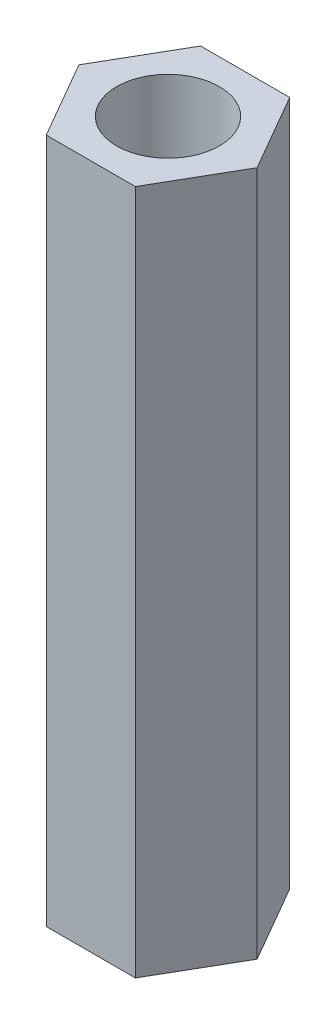
SolidWorks part; units mm, degrees
material "黄铜"
ref_plane "前视基准面" through (0, 0, 0) normal (0, 0, 1) x (1, 0, 0)
ref_plane "上视基准面" through (0, 0, 0) normal (0, 1, 0) x (1, 0, 0)
ref_plane "右视基准面" through (0, 0, 0) normal (1, 0, 0) x (0, 0, -1)
other "Configuration Table"
sketch "草图1" plane through (0, 0, 0) normal (0, 1, 0) x (1, 0, 0)
  line L1 (2.6, 0) -> (1.3, 2.2517)
  line L2 (1.3, 2.2517) -> (-1.3, 2.2517)
  line L3 (-1.3, 2.2517) -> (-2.6, 0)
  line L4 (-2.6, 0) -> (-1.3, -2.2517)
  line L5 (-1.3, -2.2517) -> (1.3, -2.2517)
  line L6 (1.3, -2.2517) -> (2.6, 0)
  circle A0 centre (0, 0) radius 2.2517 construction
  circle A1 centre (0, 0) radius 1.5
  dimension "D1" = 5.2
  dimension "D2" = 4.5033
extrude "凸台-拉伸1" add sketch "草图1" along normal blind 20
